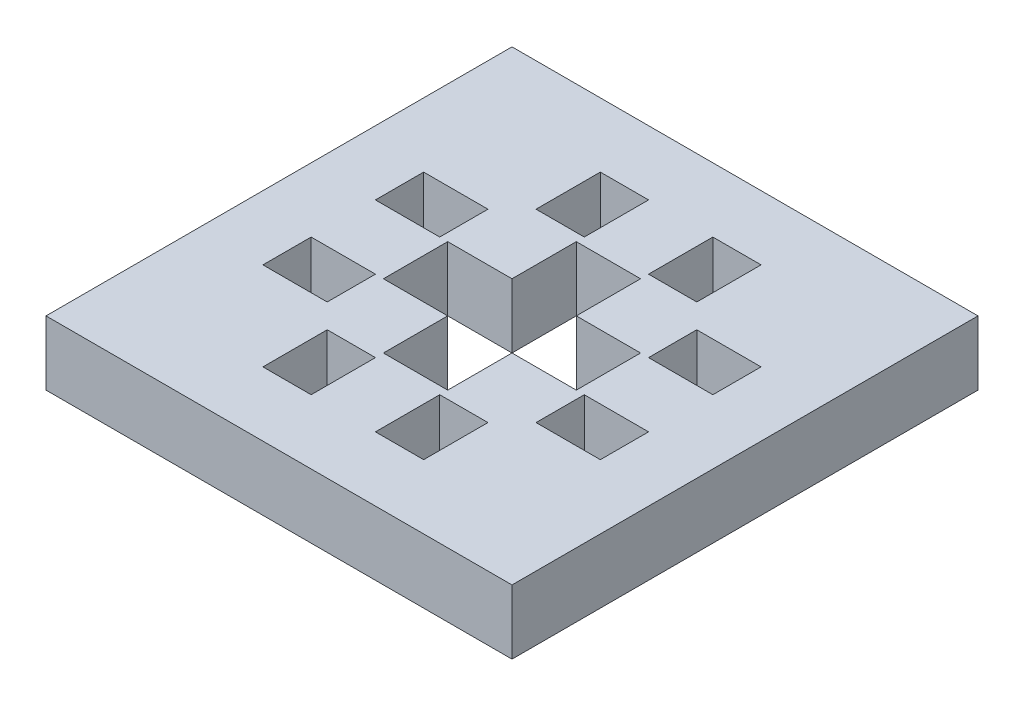
SolidWorks part; units mm, degrees
ref_plane "Front Plane" through (0, 0, 0) normal (0, 0, 1) x (1, 0, 0)
ref_plane "Top Plane" through (0, 0, 0) normal (0, 1, 0) x (1, 0, 0)
ref_plane "Right Plane" through (0, 0, 0) normal (1, 0, 0) x (0, 0, -1)
sketch "Sketch1" plane through (0, 0, 0) normal (0, 1, 0) x (1, 0, 0)
  line L0 (0.91, 15.4699) -> (0.91, -21.3499) construction
  line L1 (-17.4999, 15.4699) -> (19.3199, 15.4699)
  line L2 (-17.4999, 15.4699) -> (-17.4999, -21.3499)
  line L3 (-17.4999, -21.3499) -> (19.3199, -21.3499)
  line L4 (19.3199, 15.4699) -> (19.3199, -21.3499)
  line L5 (-17.4999, -2.94) -> (19.3199, -2.94) construction
  line L6 (-12.4199, 10.3899) -> (14.2399, 10.3899) construction
  line L7 (14.2399, 10.3899) -> (14.2399, -16.2699) construction
  line L8 (-12.4199, -16.2699) -> (14.2399, -16.2699) construction
  line L9 (-12.4199, 10.3899) -> (-12.4199, -16.2699) construction
  line L10 (0.91, 4.68) -> (3.45, 4.68)
  line L11 (3.45, 10.3899) -> (7.26, 10.3899)
  line L12 (3.45, 10.3899) -> (3.45, 5.3099)
  line L13 (3.45, 5.3099) -> (7.26, 5.3099)
  line L14 (7.26, 10.3899) -> (7.26, 5.3099)
  line L15 (-1.63, 10.3899) -> (-5.44, 10.3899)
  line L16 (-1.63, 10.3899) -> (-1.63, 5.3099)
  line L17 (-1.63, 5.3099) -> (-5.44, 5.3099)
  line L18 (-5.44, 10.3899) -> (-5.44, 5.3099)
  line L19 (3.45, 4.68) -> (3.45, -0.4)
  line L20 (3.45, -0.4) -> (8.53, -0.4)
  line L21 (8.53, -0.4) -> (8.53, -2.94)
  line L22 (8.53, -2.94) -> (8.53, -5.48)
  line L23 (14.2399, -5.48) -> (14.2399, -9.29)
  line L24 (14.2399, -5.48) -> (9.1599, -5.48)
  line L25 (9.1599, -5.48) -> (9.1599, -9.29)
  line L26 (14.2399, -9.29) -> (9.1599, -9.29)
  line L27 (14.2399, -0.4) -> (14.2399, 3.41)
  line L28 (14.2399, -0.4) -> (9.1599, -0.4)
  line L29 (9.1599, -0.4) -> (9.1599, 3.41)
  line L30 (14.2399, 3.41) -> (9.1599, 3.41)
  line L31 (8.53, -5.48) -> (3.45, -5.48)
  line L32 (3.45, -5.48) -> (3.45, -10.56)
  line L33 (3.45, -10.56) -> (0.91, -10.56)
  line L34 (0.91, -10.56) -> (-1.63, -10.56)
  line L35 (-1.63, -16.2699) -> (-5.44, -16.2699)
  line L36 (-1.63, -16.2699) -> (-1.63, -11.1899)
  line L37 (-1.63, -11.1899) -> (-5.44, -11.1899)
  line L38 (-5.44, -16.2699) -> (-5.44, -11.1899)
  line L39 (3.45, -16.2699) -> (7.26, -16.2699)
  line L40 (3.45, -16.2699) -> (3.45, -11.1899)
  line L41 (3.45, -11.1899) -> (7.26, -11.1899)
  line L42 (7.26, -16.2699) -> (7.26, -11.1899)
  line L43 (-1.63, -10.56) -> (-1.63, -5.48)
  line L44 (-1.63, -5.48) -> (-6.71, -5.48)
  line L45 (-6.71, -5.48) -> (-6.71, -2.94)
  line L46 (-6.71, -2.94) -> (-6.71, -0.4)
  line L47 (-12.4199, -0.4) -> (-12.4199, 3.41)
  line L48 (-12.4199, -0.4) -> (-7.3399, -0.4)
  line L49 (-7.3399, -0.4) -> (-7.3399, 3.41)
  line L50 (-12.4199, 3.41) -> (-7.3399, 3.41)
  line L51 (-12.4199, -5.48) -> (-12.4199, -9.29)
  line L52 (-12.4199, -5.48) -> (-7.3399, -5.48)
  line L53 (-7.3399, -5.48) -> (-7.3399, -9.29)
  line L54 (-12.4199, -9.29) -> (-7.3399, -9.29)
  line L55 (-6.71, -0.4) -> (-1.63, -0.4)
  line L56 (-1.63, -0.4) -> (-1.63, 4.68)
  line L57 (-1.63, 4.68) -> (0.91, 4.68)
  point P22 (0.91, -2.94)
  point P68 (0.91, -2.94)
  dimension "D1" = 36.8198
  dimension "D2" = 36.8198
  dimension "D4" = 5.08
  dimension "D5" = 3.81
  dimension "D6" = 2.54
  dimension "D7" = 5.08
  dimension "D8" = 2.54
  dimension "D9" = 3.81
  dimension "D10" = 2.54
  dimension "D11" = 5.08
  dimension "D12" = 2.54
  dimension "D13" = 5.08
  dimension "D3" = 5.08
  dimension "D14" = 4
extrude "Boss-Extrude1" add sketch "Sketch1" along normal blind 5.08
